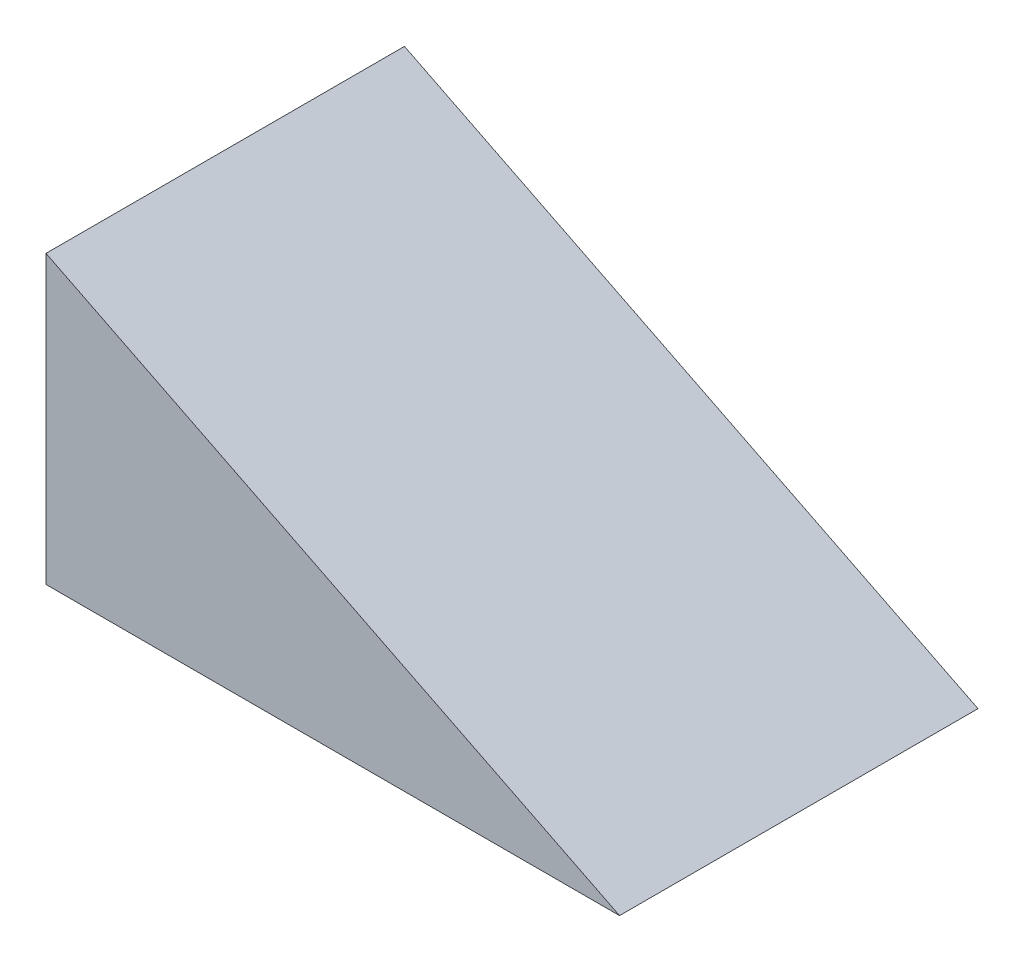
SolidWorks part; units mm, degrees
ref_plane "Front Plane" through (0, 0, 0) normal (0, 0, 1) x (1, 0, 0)
ref_plane "Top Plane" through (0, 0, 0) normal (0, 1, 0) x (1, 0, 0)
ref_plane "Right Plane" through (0, 0, 0) normal (1, 0, 0) x (0, 0, -1)
sketch "Sketch1" plane through (0, 0, 0) normal (0, 0, 1) x (1, 0, 0)
  line L0 (0, 0) -> (203.2, 0)
  line L1 (0, 0) -> (0, 101.6)
  line L2 (0, 101.6) -> (203.2, 0)
  dimension "D1" = 101.6
  dimension "D2" = 203.2
extrude "Boss-Extrude1" add sketch "Sketch1" along normal blind 127
